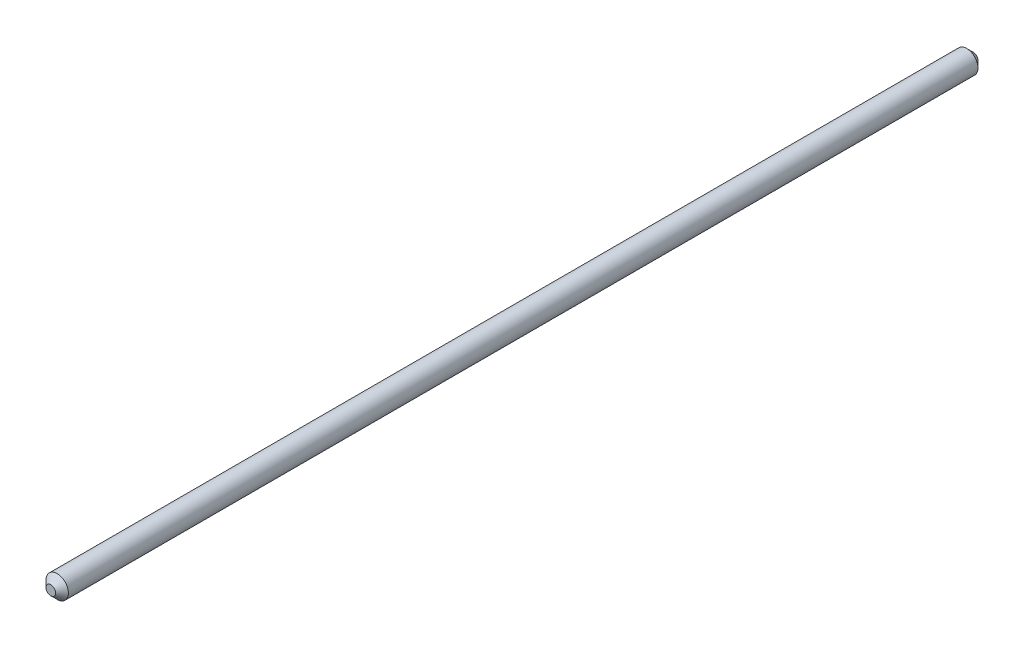
SolidWorks part; units mm, degrees
ref_plane "Front Plane" through (0, 0, 0) normal (0, 0, 1) x (1, 0, 0)
ref_plane "Top Plane" through (0, 0, 0) normal (0, 1, 0) x (1, 0, 0)
ref_plane "Right Plane" through (0, 0, 0) normal (1, 0, 0) x (0, 0, -1)
sketch "Sketch1" plane through (0, 0, 0) normal (1, 0, 0) x (0, 0, -1)
  line L0 (-162.5, 0) -> (162.5, 0) construction
  line L1 (162.5, 0) -> (162.5, 3.95)
  line L2 (162.5, 3.95) -> (-162.5, 3.95)
  line L3 (-162.5, 3.95) -> (-162.5, 0)
  line L4 (164.944, 0.3) -> (161.944, 0.3) construction
  line L5 (161.944, 0.3) -> (163.444, 6.1) construction
  line L6 (163.444, 6.1) -> (164.944, 0.3) construction
  line L7 (164, 3.95) -> (162.8879, 3.95) construction
  line L8 (164.3879, 2.45) -> (162.5, 2.45) construction
  line L9 (163.444, 2.45) -> (163.444, 0.3) construction
  line L10 (163.444, 3.95) -> (163.444, 6.1) construction
  line L15 (164.6659, 1.375) -> (164, 3.95)
  line L16 (164, 3.95) -> (162.8879, 3.95)
  line L17 (160.25, 3.95) -> (162.5, 1.7)
  line L18 (162.8879, 3.95) -> (162.222, 1.375)
  line L19 (162.222, 1.375) -> (164.6659, 1.375)
  line L20 (162.694, 3.2) -> (164.194, 3.2) construction
  line L21 (163.444, 3.95) -> (163.444, 2.45) construction
  point P15 (163.444, 1.375)
  point P21 (153.5, -3.95)
  point P23 (137.1, 0)
  point P24 (153.5, 3.95)
  point P25 (-137.1, 0)
  point P26 (72.5, 0)
  dimension "Thread Size" = 7.9
  dimension "Length" = 325
  dimension "D1" = 45
  dimension "D2" = 2.25
  dimension "D4" = 29
  dimension "Pitch" = 3
  dimension "Segment" = 90
  dimension "D3" = 9
  dimension "D5" = 25.4
  dimension "D6" = 25.4
sketch "Sketch2" plane through (0, 0, 0) normal (1, 0, 0) x (0, 0, -1)
  line L0 (-162.5, 3.95) -> (-162.5, 0) construction
  line L1 (162.5, 3.95) -> (-162.5, 3.95) construction
  line L2 (162.5, 0) -> (162.5, 3.95) construction
  line L3 (-162.5, 3.95) -> (-162.5, 0)
  line L4 (162.5, 3.95) -> (-162.5, 3.95)
  line L5 (162.5, 0) -> (162.5, 3.95)
  line L6 (-162.5, 0) -> (162.5, 0)
revolve "Revolve1" add sketch "Sketch2" angle 360 about L6
chamfer "Chamfer1" distance 2.25 angle 45 2 edges at (3.95, 0, 162.5) (3.95, 0, -162.5)
equation "\"D2@Sketch1\"=\"Pitch@Sketch1\"*0.75"
equation "\"D1@Chamfer1\" = \"Pitch@Sketch1\" * 0.75"
equation "\"Segment@Sketch1\"=\"Pitch@Sketch1\" * 30"
equation "\"D3@Sketch1\"=\"Pitch@Sketch1\"*3"
equation "\"D6@Sketch1\"=\"D5@Sketch1\""
